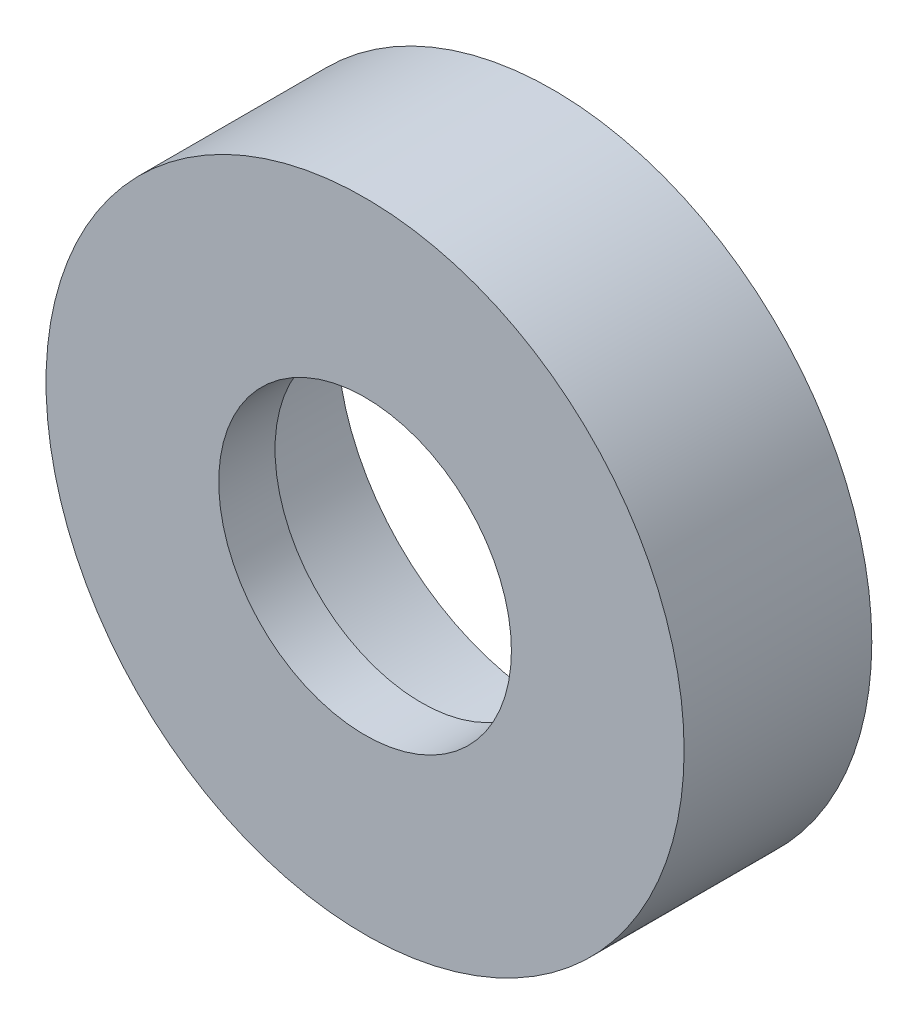
SolidWorks part; units mm, degrees
ref_plane "Спереди" through (0, 0, 0) normal (0, 0, 1) x (1, 0, 0)
ref_plane "Сверху" through (0, 0, 0) normal (0, 1, 0) x (1, 0, 0)
ref_plane "Справа" through (0, 0, 0) normal (1, 0, 0) x (0, 0, -1)
sketch "Эскиз1" plane through (0, 0, 0) normal (0, 0, 1) x (1, 0, 0)
  circle A1 centre (0, 0) radius 11.5
  circle A2 centre (0, 0) radius 17
extrude "Бобышка-Вытянуть1" add sketch "Эскиз1" along normal blind 10
sketch "Эскиз2" plane through (0, 0, 10) normal (0, 0, 1) x (1, 0, 0)
  circle A0 centre (0, 0) radius 7.7972
  circle A1 centre (0, 0) radius 11.5
extrude "Бобышка-Вытянуть2" add sketch "Эскиз2" against normal blind 3
